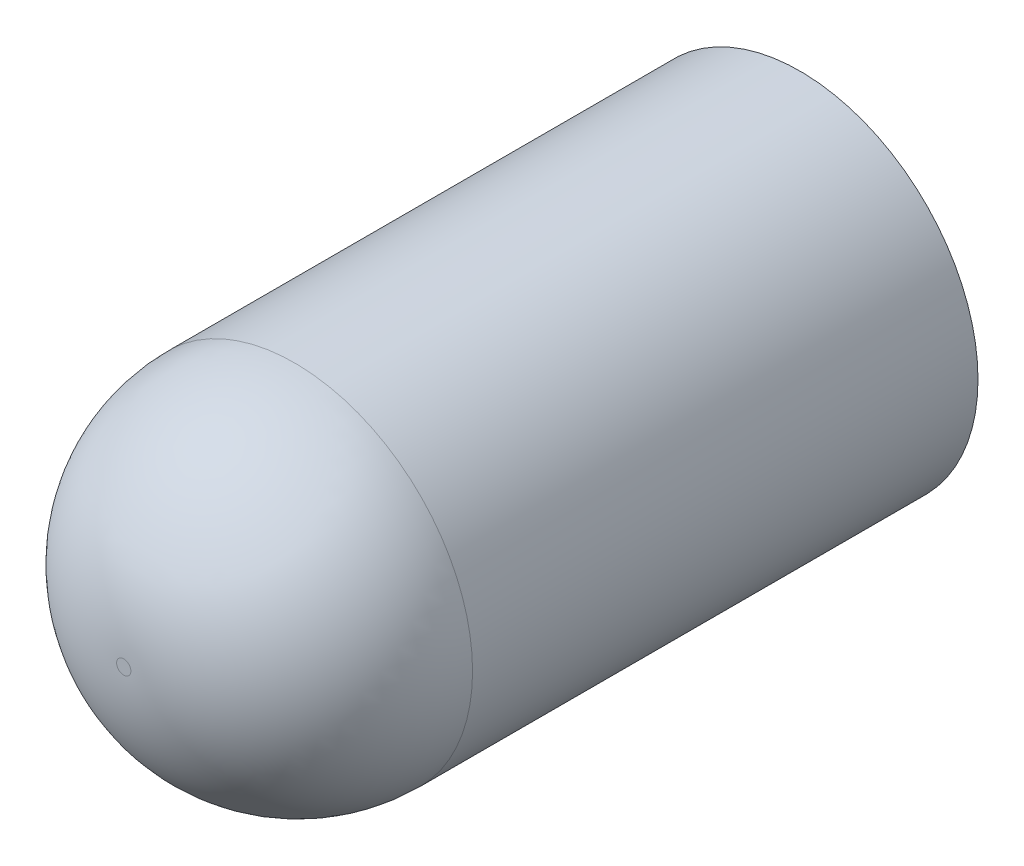
SolidWorks part; units mm, degrees
ref_plane "Спереди" through (0, 0, 0) normal (0, 0, 1) x (1, 0, 0)
ref_plane "Сверху" through (0, 0, 0) normal (0, 1, 0) x (1, 0, 0)
ref_plane "Справа" through (0, 0, 0) normal (1, 0, 0) x (0, 0, -1)
sketch "Эскиз1" plane through (0, 0, 0) normal (0, 0, 1) x (1, 0, 0)
  circle A0 centre (0, 15) radius 2.5 construction
  circle A1 centre (0, 15) radius 2.5
extrude "Бобышка-Вытянуть1" add sketch "Эскиз1" along normal blind 2.5 and the other way blind 7
fillet "Скругление1" radius 2.4 1 edges at (2.5, 15, 2.5)
